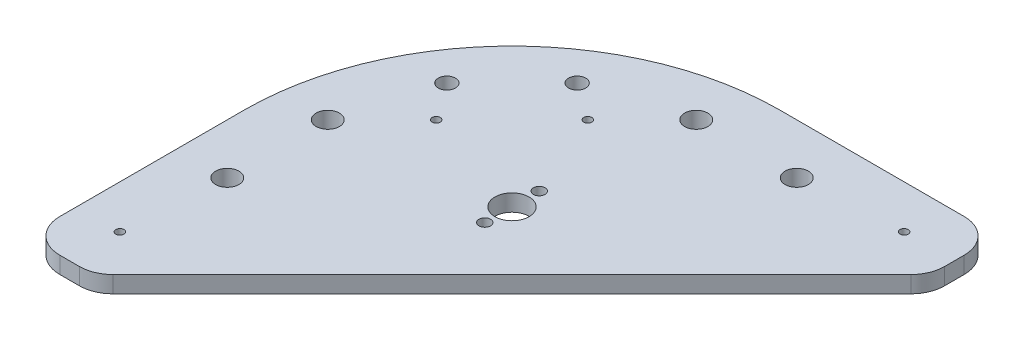
SolidWorks part; units mm, degrees
material "Acrylic (Medium-high impact)"
ref_plane "Front Plane" through (0, 0, 0) normal (0, 0, 1) x (1, 0, 0)
ref_plane "Top Plane" through (0, 0, 0) normal (0, 1, 0) x (1, 0, 0)
ref_plane "Right Plane" through (0, 0, 0) normal (1, 0, 0) x (0, 0, -1)
sketch "Sketch1" plane through (0, 0, 0) normal (0, 1, 0) x (1, 0, 0)
  line L1 (-92.075, -92.075) -> (92.075, -92.075)
  line L2 (-92.075, -92.075) -> (-92.075, 92.075)
  line L3 (-92.075, 92.075) -> (92.075, 92.075)
  line L4 (92.075, -92.075) -> (92.075, 92.075)
  line L5 (-92.075, -92.075) -> (92.075, 92.075) construction
  line L6 (-92.075, 92.075) -> (92.075, -92.075) construction
  point P0 (0, 0)
  dimension "D1" = 184.15
extrude "Boss-Extrude1" add sketch "Sketch1" along normal mid plane 6.35
sketch "Sketch2" plane through (0, 3.175, 0) normal (0, 1, 0) x (1, 0, 0)
  line L0 (92.075, -92.075) -> (92.075, 66.675)
  line L1 (92.075, -92.075) -> (92.075, 92.075) construction
  line L2 (92.075, 66.675) -> (-66.675, -92.075)
  line L3 (-92.075, -92.075) -> (92.075, -92.075) construction
  line L4 (-66.675, -92.075) -> (92.075, -92.075)
  dimension "D1" = 158.75
extrude "Cut-Extrude1" cut sketch "Sketch2" against normal through all
sketch "Sketch3" plane through (0, 3.175, 0) normal (0, 1, 0) x (1, 0, 0)
  line L0 (-92.075, -92.075) -> (-66.675, -92.075) construction
  line L1 (92.075, 66.675) -> (92.075, 92.075) construction
  line L2 (-9.525, 19.8438) -> (-9.525, -0.7937) construction
  line L3 (-92.075, -92.075) -> (-66.675, -92.075) construction
  line L4 (-9.525, 9.525) -> (92.075, 9.525) construction
  line L5 (-9.525, 9.525) -> (-9.525, -92.075) construction
  line L6 (-9.525, -92.075) -> (92.075, -92.075) construction
  line L7 (92.075, 9.525) -> (92.075, -92.075) construction
  circle A0 centre (-9.525, 9.525) radius 6.477
  circle A1 centre (-9.525, 19.8438) radius 2.2034
  circle A2 centre (-9.525, -0.7937) radius 2.2034
  point P10 (-9.525, 9.525)
  dimension "D1" = 12.954
  dimension "D4" = 4.4069
  dimension "D2" = 101.6
  dimension "D3" = 101.6
  dimension "D5" = 10.3187
extrude "Cut-Extrude2" cut sketch "Sketch3" against normal through all
hole_wizard " (0.332) Diameter Hole1" positions "Sketch4" profile "Sketch5" hole size "S" standard "ANSI Inch" end condition through all
sketch "Sketch4" plane through (0, 3.175, 0) normal (0, 1, 0) x (1, 0, 0)
  line L12 (73.025, -73.025) -> (-73.025, -73.025) construction
  line L13 (73.025, -73.025) -> (73.025, 73.025) construction
  line L14 (73.025, 73.025) -> (-73.025, 73.025) construction
  line L15 (-73.025, -73.025) -> (-73.025, 73.025) construction
  line L21 (92.075, 66.675) -> (92.075, 92.075) construction
  line L22 (-92.075, -92.075) -> (-66.675, -92.075) construction
  point P317 (-3.175, 73.025)
  point P319 (34.925, 73.025)
  point P321 (-73.025, 3.175)
  point P323 (-73.025, -34.925)
  dimension "D2" = 19.05
  dimension "D3" = 19.05
  dimension "D4" = 57.15
  dimension "D5" = 38.1
  dimension "D6" = 57.15
  dimension "D7" = 38.1
  dimension "D10" = 146.05
sketch "Sketch5" plane through (-73.025, 3.175, 34.925) normal (1, 0, 0) x (0, 0, 1)
  line L0 (0, 0) -> (0, 6.35)
  line L1 (0, 6.35) -> (4.4196, 6.35)
  line L2 (4.4196, 6.35) -> (4.4196, 0)
  line L5 (4.4196, 0) -> (0, 0)
  line L11 (0, -6.35) -> (0, 107.95) construction
  dimension "Thru Hole Dia." = 8.8392
  dimension "Thru Hole Depth" = 6.35
fillet "Fillet1" radius 12.7 4 edges at (92.075, 0, -92.075) (92.075, 0, -66.675) (-66.675, 0, 92.075) (-92.075, 0, 92.075)
fillet "Fillet2" radius 101.6 1 edges at (-92.075, 0, -92.075)
sketch "Sketch6" plane through (0, -3.175, 0) normal (0, -1, 0) x (1, 0, 0)
  line L0 (73.025, -75.6553) -> (-75.6553, 73.025) construction
  line L1 (-1.6617, -1.6617) -> (-77.5439, -77.5439) construction
  line L2 (-6.3001, -69.8999) -> (-69.8999, -6.3001) construction
  line L3 (88.3553, -62.9553) -> (-62.9553, 88.3553) construction
  line L4 (92.075, -71.9355) -> (92.075, -79.375) construction
  line L5 (-79.375, 92.075) -> (-71.9355, 92.075) construction
  circle A0 centre (73.025, -75.6553) radius 1.5367
  circle A1 centre (-23.7316, -52.4684) radius 1.5367
  circle A2 centre (-75.6553, 73.025) radius 1.5367
  circle A3 centre (-52.4684, -23.7316) radius 1.5367
  circle A4 centre (-73.025, -3.175) radius 4.4196 construction
  circle A5 centre (-3.175, -73.025) radius 4.4196 construction
  point P8 (-75.6553, 92.075)
  point P10 (92.075, -75.6553)
  point P25 (-38.1, -38.1)
  point P35 (-3.175, -73.025)
  dimension "D2" = 3.0734
  dimension "D1" = 19.05
  dimension "D3" = 20.32
extrude "Cut-Extrude3" cut sketch "Sketch6" against normal through all and the other way through all
sketch "Sketch7" plane through (0, -3.175, 0) normal (0, -1, 0) x (1, 0, 0)
  line L0 (-21.3815, -21.3815) -> (-5.1863, -5.1863) construction
  line L2 (88.3553, -62.9553) -> (-62.9553, 88.3553) construction
  line L3 (-37.8139, -62.5096) -> (-62.5096, -37.8139) construction
  circle A0 centre (-50.1618, -50.1618) radius 12.827
  circle A1 centre (-37.8139, -62.5096) radius 3.2639
  circle A2 centre (-62.5096, -37.8139) radius 3.2639
  point P6 (12.7, 12.7)
  dimension "D3" = 88.9
  dimension "D1" = 25.654
  dimension "D4" = 6.5278
  dimension "D2" = 34.925
extrude "Cut-Extrude4" cut sketch "Sketch7" against normal through all
sketch "Sketch8" plane through (0, -3.175, 0) normal (0, -1, 0) x (1, 0, 0)
  circle A0 centre (-50.1618, -50.1618) radius 12.827
  circle A1 centre (-50.1618, -50.1618) radius 12.827 construction
extrude "Boss-Extrude2" add sketch "Sketch8" against normal up to surface (6.35 mm away) up to face at (-37.8139, 3.175, -65.7735)
